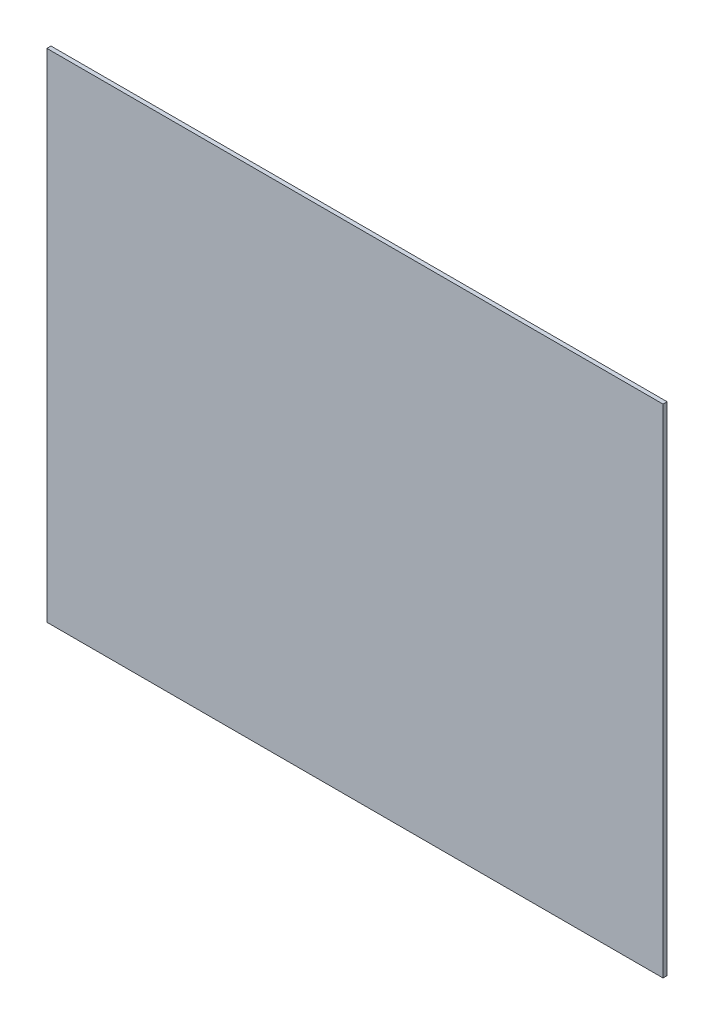
SolidWorks part; units mm, degrees
ref_plane "Front Plane" through (0, 0, 0) normal (0, 0, 1) x (1, 0, 0)
ref_plane "Top Plane" through (0, 0, 0) normal (0, 1, 0) x (1, 0, 0)
ref_plane "Right Plane" through (0, 0, 0) normal (1, 0, 0) x (0, 0, -1)
sketch "Sketch1" plane through (0, 0, 0) normal (0, 0, 1) x (1, 0, 0)
  line L1 (-238.125, -192.0875) -> (238.125, -192.0875)
  line L2 (-238.125, -192.0875) -> (-238.125, 192.0875)
  line L3 (-238.125, 192.0875) -> (238.125, 192.0875)
  line L4 (238.125, -192.0875) -> (238.125, 192.0875)
  line L5 (-238.125, -192.0875) -> (238.125, 192.0875) construction
  line L6 (-238.125, 192.0875) -> (238.125, -192.0875) construction
  point P0 (0, 0)
  dimension "D1" = 476.25
  dimension "D2" = 384.175
extrude "Boss-Extrude1" add sketch "Sketch1" along normal blind 3.175
